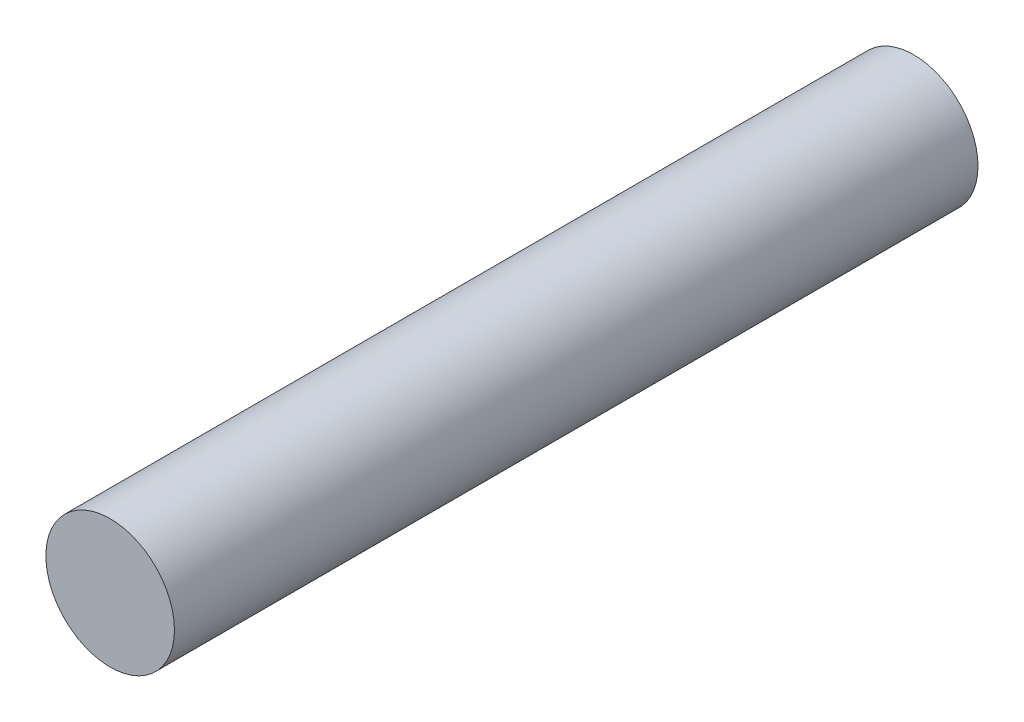
SolidWorks part; units mm, degrees
material "铸造不锈钢"
ref_plane "前视基准面" through (0, 0, 0) normal (0, 0, 1) x (1, 0, 0)
ref_plane "上视基准面" through (0, 0, 0) normal (0, 1, 0) x (1, 0, 0)
ref_plane "右视基准面" through (0, 0, 0) normal (1, 0, 0) x (0, 0, -1)
sketch "草图1" plane through (0, 0, 0) normal (0, 0, 1) x (1, 0, 0)
  circle A0 centre (0, 0) radius 0.4
extrude "凸台-拉伸1" add sketch "草图1" along normal blind 5
cosmetic thread "装饰螺纹线1" parameters "D2"=0.2
